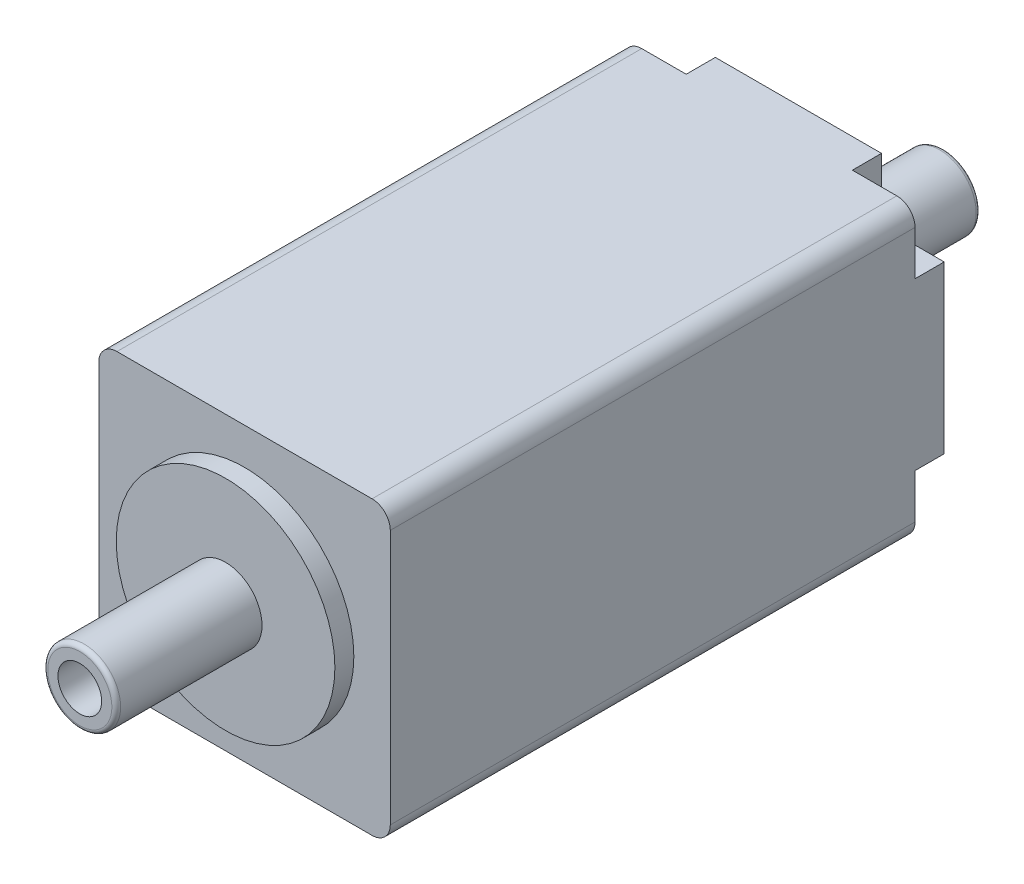
SolidWorks part; units mm, degrees
material "6063-T5"
ref_plane "Front Plane" through (0, 0, 0) normal (1, 0, 0) x (0, 1, 0)
ref_plane "Top Plane" through (0, 0, 0) normal (0, 0, 1) x (0, 1, 0)
ref_plane "Right Plane" through (0, 0, 0) normal (0, 1, 0) x (-1, 0, 0)
sketch "Sketch1" plane through (0, 0, 0) normal (0, 0, 1) x (0, 1, 0)
  line L1 (-8.75, -10) -> (8.75, -10)
  line L2 (-10, -8.75) -> (-10, 8.75)
  line L3 (-8.75, 10) -> (8.75, 10)
  line L4 (10, -8.75) -> (10, 8.75)
  line L5 (-10, -10) -> (10, 10) construction
  line L6 (-10, 10) -> (10, -10) construction
  arc A0 (8.75, 10) -> (10, 8.75) centre (8.75, 8.75) cw
  arc A1 (8.75, -10) -> (10, -8.75) centre (8.75, -8.75) ccw
  arc A2 (-8.75, -10) -> (-10, -8.75) centre (-8.75, -8.75) cw
  arc A3 (-10, 8.75) -> (-8.75, 10) centre (-8.75, 8.75) cw
  circle A5 centre (0, 0) radius 1.5
  point P0 (0, 0)
  dimension "D3" = 1.25
  dimension "D5" = 3
  dimension "D1" = 20
  dimension "D2" = 20
extrude "Boss-Extrude1" add sketch "Sketch1" against normal blind 38
sketch "Sketch3" plane through (0, 0, 0) normal (0, 0, 1) x (1, 0, 0)
  circle A0 centre (0, 0) radius 7.5
  circle A1 centre (0, 0) radius 1.5
  circle A2 centre (0, 0) radius 1.5 construction
  dimension "D1" = 15
extrude "Boss-Extrude2" add sketch "Sketch3" along normal blind 1.3
sketch "Sketch4" plane through (0, 0, -38) normal (0, 0, -1) x (1, 0, 0)
  line L2 (-10, 5.7) -> (-10, 10)
  line L3 (-10, 10) -> (-5.7, 10)
  line L4 (-10, 5.7) -> (-7.2, 5.7)
  line L5 (-5.7, 7.2) -> (-5.7, 10)
  line L6 (7.2, 5.7) -> (10, 5.7)
  line L7 (10, 10) -> (10, 5.7)
  line L8 (5.7, 10) -> (10, 10)
  line L9 (5.7, 10) -> (5.7, 7.2)
  line L10 (5.7, -7.2) -> (5.7, -10)
  line L11 (10, -10) -> (5.7, -10)
  line L12 (10, -5.7) -> (10, -10)
  line L13 (10, -5.7) -> (7.2, -5.7)
  line L14 (-7.2, -5.7) -> (-10, -5.7)
  line L15 (-10, -10) -> (-10, -5.7)
  line L16 (-5.7, -10) -> (-10, -10)
  line L17 (-5.7, -10) -> (-5.7, -7.2)
  line L18 (-10, 8.75) -> (-10, -8.75) construction
  line L19 (8.75, 10) -> (-8.75, 10) construction
  arc A1 (-7.2, 5.7) -> (-5.7, 7.2) centre (-7.2, 7.2) ccw
  arc A2 (5.7, 7.2) -> (7.2, 5.7) centre (7.2, 7.2) ccw
  arc A3 (7.2, -5.7) -> (5.7, -7.2) centre (7.2, -7.2) ccw
  arc A4 (-5.7, -7.2) -> (-7.2, -5.7) centre (-7.2, -7.2) ccw
  point P32 (0, 0)
  dimension "D1" = 1.5
  dimension "D2" = 4.3
  dimension "D3" = 4
extrude "Cut-Extrude1" cut sketch "Sketch4" against normal blind 2
sketch "Sketch5" plane through (0, 0, -36) normal (0, 0, -1) x (1, 0, 0)
  line L1 (-7.7, -7.7) -> (7.7, -7.7) construction
  line L2 (-7.7, -7.7) -> (-7.7, 7.7) construction
  line L3 (-7.7, 7.7) -> (7.7, 7.7) construction
  line L4 (7.7, -7.7) -> (7.7, 7.7) construction
  line L5 (-7.7, -7.7) -> (7.7, 7.7) construction
  line L6 (-7.7, 7.7) -> (7.7, -7.7) construction
  circle A0 centre (-7.7, 7.7) radius 1.05
  circle A1 centre (7.7, 7.7) radius 1.05
  circle A2 centre (7.7, -7.7) radius 1.05
  circle A3 centre (-7.7, -7.7) radius 1.05
  point P0 (0, 0)
  dimension "D1" = 15.4
  dimension "D2" = 2.1
extrude "Cut-Extrude2" cut sketch "Sketch5" against normal blind 4 contours L4 A1 L3 | L2 A3 L1 | L3 A0 L2 | A2
sketch "Sketch6" plane through (0, 0, 1.3) normal (0, 0, 1) x (1, 0, 0)
  circle A0 centre (0, 0) radius 1.5
  circle A1 centre (0, 0) radius 2.5
  circle A2 centre (0, 0) radius 1.5 construction
  dimension "D1" = 5
extrude "Boss-Extrude3" add sketch "Sketch6" along normal blind 10
sketch "Sketch7" plane through (0, 0, -38) normal (0, 0, -1) x (1, 0, 0)
  circle A0 centre (0, 0) radius 1.5
  circle A1 centre (0, 0) radius 1.5 construction
  circle A2 centre (0, 0) radius 2.5
  dimension "D1" = 5
extrude "Boss-Extrude4" add sketch "Sketch7" along normal blind 10
fillet "Fillet1" radius 0.3 2 edges at (-2.5, 0, -48) (2.5, 0, 11.3)
